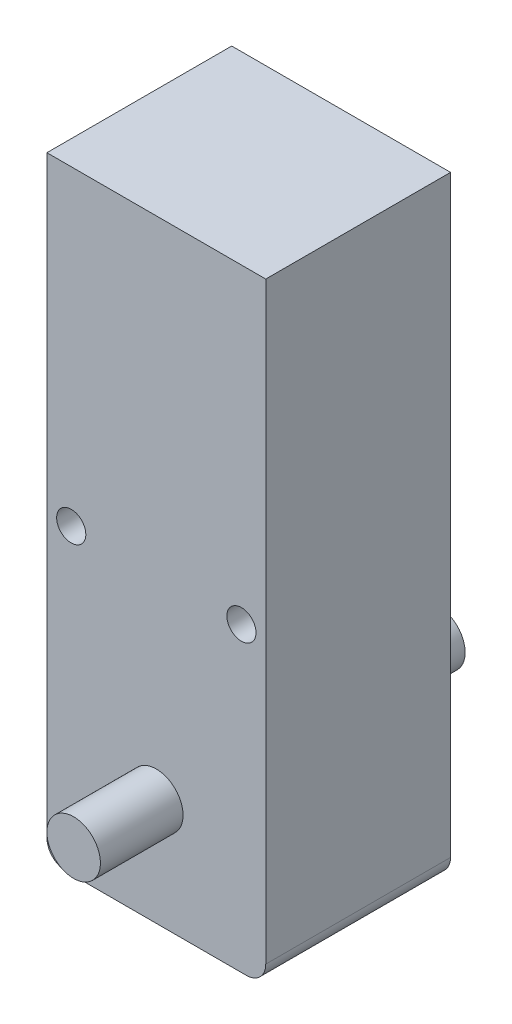
SolidWorks part; units mm, degrees
ref_plane "Front" through (0, 0, 0) normal (0, 0, 1) x (1, 0, 0)
ref_plane "Top" through (0, 0, 0) normal (0, 1, 0) x (1, 0, 0)
ref_plane "Right" through (0, 0, 0) normal (1, 0, 0) x (0, 0, -1)
sketch "Sketch1" plane through (0, 0, 0) normal (0, 1, 0) x (1, 0, 0)
  line L1 (0, 0) -> (22.5, 0)
  line L2 (0, 0) -> (0, 19)
  line L3 (0, 19) -> (22.5, 19)
  line L4 (22.5, 0) -> (22.5, 19)
  dimension "D1" = 22.5
  dimension "D2" = 19
extrude "Boss-Extrude1" add sketch "Sketch1" along normal blind 63
fillet "Fillet1" radius 2 2 edges at (22.5, 0, -9.5) (0, 0, -9.5)
sketch "Sketch2" plane through (0, 0, -19) normal (0, 0, -1) x (-1, 0, 0)
  line L0 (-20.5, 0) -> (-2, 0) construction
  line L1 (0, 63) -> (0, 2) construction
  circle A0 centre (-11.25, 11) radius 2.75
  dimension "D1" = 5.5
  dimension "D2" = 11
  dimension "D3" = 11.25
extrude "Boss-Extrude2" add sketch "Sketch2" along normal blind 10 and the other way blind 27.5
sketch "Sketch3" plane through (0, 0, 0) normal (0, -1, 0) x (1, 0, 0)
  line L0 (22.5, 0) -> (22.5, -19) construction
  line L1 (8.75, -7.0178) -> (13.75, -7.0178)
  line L2 (8.75, -7.0178) -> (8.75, -10.0178)
  line L3 (8.75, -10.0178) -> (13.75, -10.0178)
  line L4 (13.75, -7.0178) -> (13.75, -10.0178)
  dimension "D1" = 5
  dimension "D2" = 3
  dimension "D3" = 8.75
extrude "Boss-Extrude3" add sketch "Sketch3" along normal blind 6
sketch "Sketch4" plane through (0, 0, -10.0178) normal (0, 0, -1) x (-1, 0, 0)
  line L0 (-8.75, -6) -> (-13.75, -6) construction
  line L1 (-13.75, -6) -> (-13.75, 0) construction
  circle A0 centre (-11.25, -3) radius 1.5
  dimension "D1" = 3
  dimension "D2" = 3
  dimension "D3" = 2.5
extrude "Cut-Extrude1" cut sketch "Sketch4" against normal blind 10
sketch "Sketch5" plane through (0, 0, 0) normal (0, 0, 1) x (1, 0, 0)
  line L0 (2, 0) -> (20.5, 0) construction
  line L1 (0, 63) -> (0, 2) construction
  line L2 (22.5, 63) -> (22.5, 2) construction
  circle A0 centre (20, 31) radius 1.5
  circle A1 centre (2.5, 31) radius 1.5
  point P6 (0, 0)
  dimension "D2" = 3
  dimension "D1" = 31
  dimension "D3" = 2.5
  dimension "D4" = 2.5
extrude "Cut-Extrude2" cut sketch "Sketch5" against normal through all
